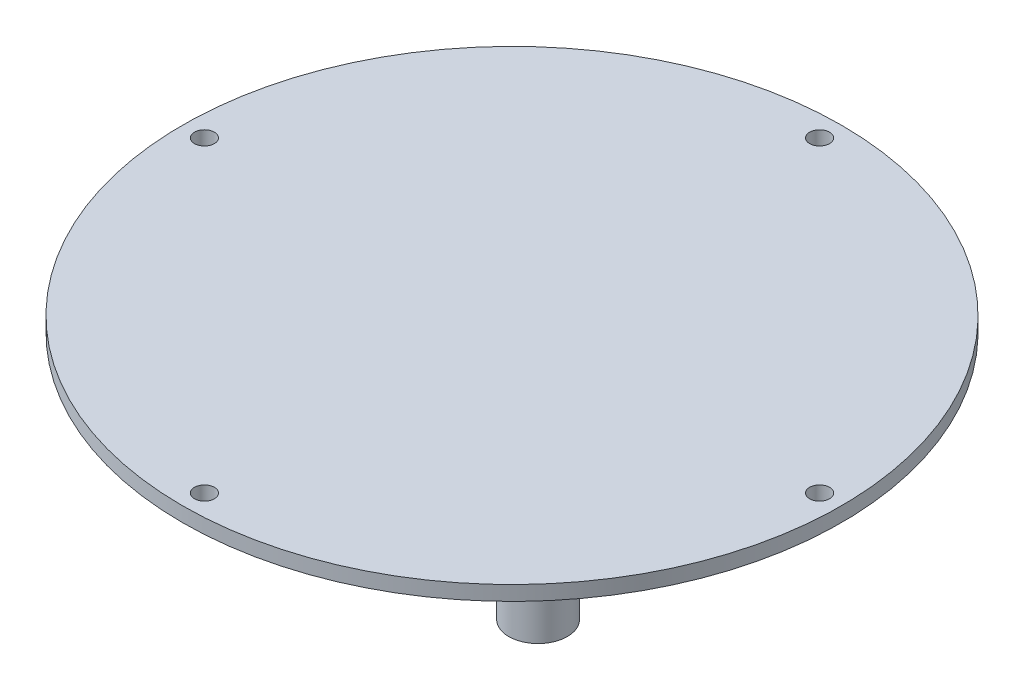
SolidWorks part; units mm, degrees
material "AISI 316 Stainless Steel Sheet (SS)"
ref_plane "Front Plane" through (0, 0, 0) normal (0, 0, 1) x (1, 0, 0)
ref_plane "Top Plane" through (0, 0, 0) normal (0, 1, 0) x (1, 0, 0)
ref_plane "Right Plane" through (0, 0, 0) normal (1, 0, 0) x (0, 0, -1)
sketch "Sketch2" plane through (0, 0, 0) normal (0, 1, 0) x (1, 0, 0)
  circle A0 centre (0, 0) radius 57.15
  dimension "D1" = 114.3
extrude "Boss-Extrude1" add sketch "Sketch2" along normal blind 2.54
sketch "Sketch3" plane through (0, 0, 0) normal (0, -1, 0) x (1, 0, 0)
  circle A0 centre (-32.7104, -28.1876) radius 5.08
  dimension "D2" = 10.16
  dimension "D3" = 34.9303
  dimension "D1" = 43.18
extrude "Boss-Extrude2" add sketch "Sketch3" along normal blind 12.7 contours A0
pattern_circular "CirPattern1" count 4 over 360 about axis through (0, 0, 0) along (0, 1, 0) of "Boss-Extrude2"
sketch "Sketch4" plane through (0, 2.54, 0) normal (0, 1, 0) x (1, 0, 0)
  point P0 (-53.34, 0)
hole_wizard "#8-32 Tapped Hole1" positions "Sketch4" profile "Sketch5" tap size "#8-32" standard "ANSI Inch" end condition through all
sketch "Sketch5" plane through (-53.34, 2.54, 0) normal (1, 0, 0) x (0, 0, 1)
  line L0 (0, 0) -> (0, 15.24)
  line L1 (0, 15.24) -> (1.7272, 15.24)
  line L2 (1.7272, 15.24) -> (1.7272, 0)
  line L5 (1.7272, 0) -> (0, 0)
  line L11 (0, -6.35) -> (0, 107.95) construction
  dimension "Thru Tap Drill Dia." = 3.4544
  dimension "Thru Tap Drill Depth" = 15.24
cosmetic thread "Hole Thread1" parameters "D2"=4.1656
pattern_circular "CirPattern2" count 4 over 360 about axis through (0, 0, 0) along (0, 1, 0) of "#8-32 Tapped Hole1"
cosmetic thread "Hole Thread2" parameters "D2"=4.1656
cosmetic thread "Hole Thread3" parameters "D2"=4.1656
cosmetic thread "Hole Thread4" parameters "D2"=4.1656
